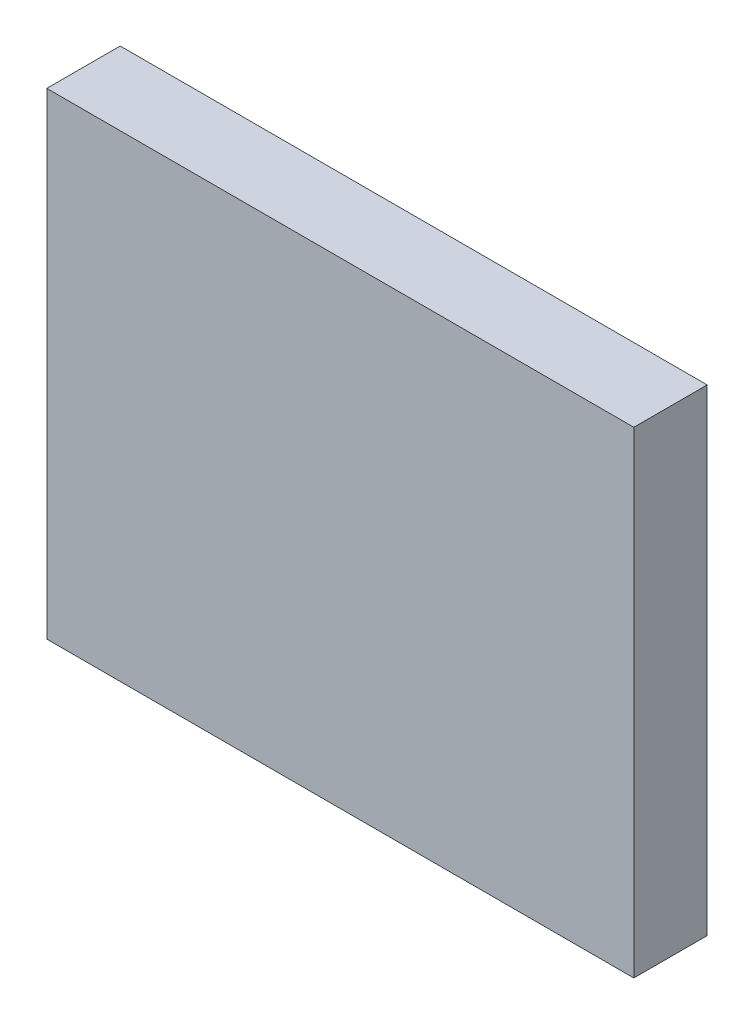
SolidWorks part; units mm, degrees
ref_plane "Front Plane" through (0, 0, 0) normal (0, 0, 1) x (1, 0, 0)
ref_plane "Top Plane" through (0, 0, 0) normal (0, 1, 0) x (1, 0, 0)
ref_plane "Right Plane" through (0, 0, 0) normal (1, 0, 0) x (0, 0, -1)
sketch "Sketch1" plane through (0, 0, 0) normal (0, 0, 1) x (1, 0, 0)
  line L1 (0, 0) -> (-160, 0)
  line L2 (0, 0) -> (0, 130)
  line L3 (0, 130) -> (-160, 130)
  line L4 (-160, 0) -> (-160, 130)
extrude "Boss-Extrude1" add sketch "Sketch1" along normal blind 20
sketch "Sketch2" plane through (0, 0, 0) normal (0, 0, -1) x (-1, 0, 0)
  line L4 (150, 110) -> (150, 20)
  line L5 (20, 120) -> (140, 120)
  line L6 (10, 20) -> (10, 110)
  line L7 (140, 10) -> (20, 10)
  arc A4 (140, 10) -> (150, 20) centre (140, 20) ccw
  arc A5 (150, 110) -> (140, 120) centre (140, 110) ccw
  arc A6 (20, 120) -> (10, 110) centre (20, 110) ccw
  arc A7 (10, 20) -> (20, 10) centre (20, 20) ccw
extrude "Cut-Extrude1" cut sketch "Sketch2" against normal blind 10
sketch "Sketch3" plane through (0, 0, 10) normal (0, 0, -1) x (-1, 0, 0)
  circle A4 centre (142.1213, 112.1213) radius 1.7
  circle A5 centre (142.1213, 17.8787) radius 1.7
  circle A6 centre (17.8787, 17.8787) radius 1.7
  circle A7 centre (17.8787, 112.1213) radius 1.7
extrude "Cut-Extrude2" [suppressed] cut sketch "Sketch3" against normal blind 10
